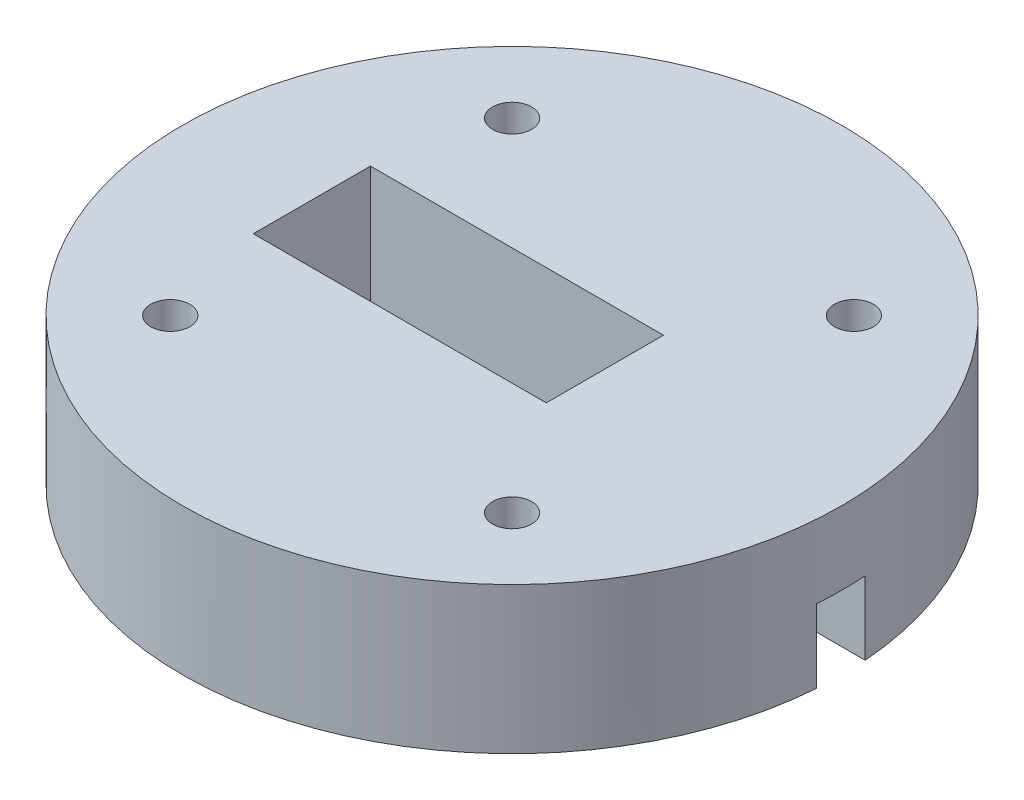
SolidWorks part; units mm, degrees
material "1.0503 (C45)"
ref_plane "前视基准面" through (0, 0, 0) normal (0, 0, 1) x (1, 0, 0)
ref_plane "上视基准面" through (0, 0, 0) normal (0, 1, 0) x (1, 0, 0)
ref_plane "右视基准面" through (0, 0, 0) normal (1, 0, 0) x (0, 0, -1)
sketch "草图1" plane through (0, 0, 0) normal (0, 1, 0) x (1, 0, 0)
  circle A0 centre (0, 0) radius 67.5
  dimension "D1" = 135
extrude "凸台-拉伸1" add sketch "草图1" along normal blind 30
sketch "草图2" plane through (0, 30, 0) normal (0, 1, 0) x (1, 0, 0)
  line L0 (-67.5, 0) -> (67.5, 0) construction
  line L2 (-41, -12) -> (19, -12)
  line L3 (-41, -12) -> (-41, 12)
  line L4 (-41, 12) -> (19, 12)
  line L5 (19, -12) -> (19, 12)
  line L6 (-41, -12) -> (19, 12) construction
  line L7 (-41, 12) -> (19, -12) construction
  circle A0 centre (0, 0) radius 67.5 construction
  point P5 (-11, 0)
  dimension "D1" = 24
  dimension "D2" = 60
  dimension "D3" = 19
extrude "切除-拉伸1" cut sketch "草图2" against normal through all
sketch "草图3" plane through (0, 0, 0) normal (1, 0, 0) x (0, 0, -1)
  line L0 (0, 0) -> (0, 61.3027) construction
  line L2 (-5, 0) -> (5, 0)
  line L3 (-5, 0) -> (-5, 15)
  line L4 (-5, 15) -> (5, 15)
  line L5 (5, 0) -> (5, 15)
  line L6 (-5, 0) -> (5, 15) construction
  line L7 (-5, 15) -> (5, 0) construction
  line L8 (-67.5, 0) -> (67.5, 0) construction
  point P3 (0, 7.5)
  dimension "D1" = 15
  dimension "D2" = 10
extrude "切除-拉伸2" cut sketch "草图3" along normal blind 97
sketch "草图4" plane through (0, 30, 0) normal (0, 1, 0) x (1, 0, 0)
  line L0 (0, 0) -> (35.0018, 35.0018) construction
  circle A0 centre (35.0018, 35.0018) radius 4
  circle A1 centre (35.0018, -35.0018) radius 4
  circle A2 centre (-35.0018, -35.0018) radius 4
  circle A3 centre (-35.0018, 35.0018) radius 4
  point P13 (0, 0)
  dimension "D2" = 8
  dimension "D1" = 49.5
  dimension "D3" = 4
extrude "切除-拉伸3" cut sketch "草图4" against normal through all
